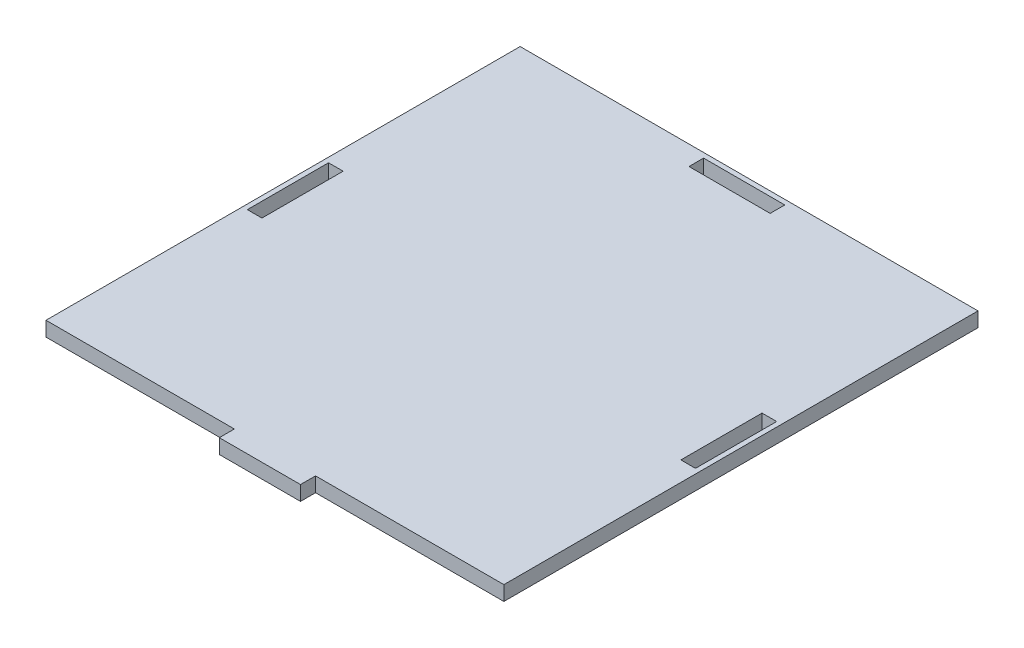
SolidWorks part; units mm, degrees
ref_plane "Front Plane" through (0, 0, 0) normal (0, 0, 1) x (1, 0, 0)
ref_plane "Top Plane" through (0, 0, 0) normal (0, 1, 0) x (1, 0, 0)
ref_plane "Right Plane" through (0, 0, 0) normal (1, 0, 0) x (0, 0, -1)
sketch "Sketch1" plane through (0, 0, 0) normal (0, 1, 0) x (1, 0, 0)
  line L0 (0, 0) -> (0, -292) construction
  line L1 (-282, 292) -> (282, 292)
  line L2 (-282, 292) -> (-282, -292)
  line L3 (-282, -292) -> (-50, -292)
  line L4 (282, 292) -> (282, -292)
  line L5 (-282, 292) -> (282, -292) construction
  line L6 (-282, -292) -> (282, 292) construction
  line L7 (0, 0) -> (371.1371, 0) construction
  line L8 (-50, -268) -> (50, -268)
  line L9 (-50, -268) -> (-50, -286)
  line L10 (-50, -286) -> (50, -286)
  line L11 (50, -268) -> (50, -286)
  line L12 (-50, -268) -> (50, -286) construction
  line L13 (-50, -286) -> (50, -268) construction
  line L14 (-276, 9) -> (-276, -9)
  line L15 (276, 9) -> (176, 9)
  line L16 (276, 9) -> (276, -9)
  line L17 (276, -9) -> (176, -9)
  line L18 (176, 9) -> (176, -9)
  line L19 (276, 9) -> (176, -9) construction
  line L20 (276, -9) -> (176, 9) construction
  line L21 (-276, 9) -> (-176, 9)
  line L22 (-176, 9) -> (-176, -9)
  line L23 (-276, -9) -> (-176, -9)
  line L24 (-50, -292) -> (-50, -310.518)
  line L25 (-50, -310.518) -> (50, -310.518)
  line L26 (50, -310.518) -> (50, -292)
  line L28 (50, -292) -> (282, -292)
  line L29 (0, -310.518) -> (0, -361.6926) construction
  line L30 (-50, 268) -> (-50, 286)
  line L31 (-50, 286) -> (50, 286)
  line L32 (-50, 268) -> (50, 268)
  line L33 (50, 268) -> (50, 286)
  point P0 (0, 0)
  point P8 (0, -277)
  point P13 (226, 0)
  dimension "D1" = 564
  dimension "D2" = 584
  dimension "D3" = 6
  dimension "D4" = 18
  dimension "D5" = 100
  dimension "D6" = 6
  dimension "D7" = 100
  dimension "D8" = 18
extrude "Boss-Extrude2" add sketch "Sketch1" along normal blind 18 contours L1 L4 L28 L26 L25 L24 L3 L2
sketch "Sketch2" plane through (0, 0, 0) normal (0, -1, 0) x (1, 0, 0)
  line L0 (0, 0) -> (450.014, 0) construction
  line L1 (0, 0) -> (0, -217.5622) construction
  line L2 (282, -292) -> (282, 292) construction
  line L3 (258, 50) -> (276, 50)
  line L4 (258, 50) -> (258, -50)
  line L5 (258, -50) -> (276, -50)
  line L6 (276, 50) -> (276, -50)
  line L7 (258, 50) -> (276, -50) construction
  line L8 (258, -50) -> (276, 50) construction
  line L9 (-258, -50) -> (-276, -50)
  line L10 (-258, 50) -> (-276, 50)
  line L11 (-276, 50) -> (-276, -50)
  line L12 (-258, 50) -> (-258, -50)
  line L13 (282, -292) -> (0, -292)
  line L18 (-282, -292) -> (282, -292) construction
  line L20 (50, -292) -> (50, -310)
  line L21 (50, -310) -> (-50, -310)
  line L22 (-50, -292) -> (-50, -310)
  line L23 (0, -292) -> (-50, -310) construction
  line L24 (50, -310) -> (0, -292) construction
  line L25 (-50, -292) -> (-282, -292)
  line L26 (50, -292) -> (-50, -292)
  point P3 (267, 0)
  point P15 (0, -292)
  dimension "D1" = 6
  dimension "D2" = 18
  dimension "D3" = 100
  dimension "D5" = 100
extrude "Cut-Extrude1" cut sketch "Sketch2" against normal blind 18 contours L6 L3 L4 L5 | L12 L9 L11 L10
sketch "Sketch3" plane through (0, 0, 0) normal (0, -1, 0) x (1, 0, 0)
  line L0 (0, 0) -> (0, -277) construction
  line L7 (-282, -292) -> (282, -292) construction
  line L8 (-50, -268) -> (50, -268)
  line L9 (-50, -268) -> (-50, -286)
  line L10 (-50, -286) -> (50, -286)
  line L11 (50, -268) -> (50, -286)
  line L12 (-50, -268) -> (50, -286) construction
  line L13 (-50, -286) -> (50, -268) construction
  dimension "D1" = 6
  dimension "D2" = 18
  dimension "D3" = 100
ref_plane "Plane1" through (282, 18, -292) normal (1, 0, 0) x (0, 0, -1)
extrude "Cut-Extrude2" cut sketch "Sketch3" against normal blind 18 contours L9 L8 L11 L10
